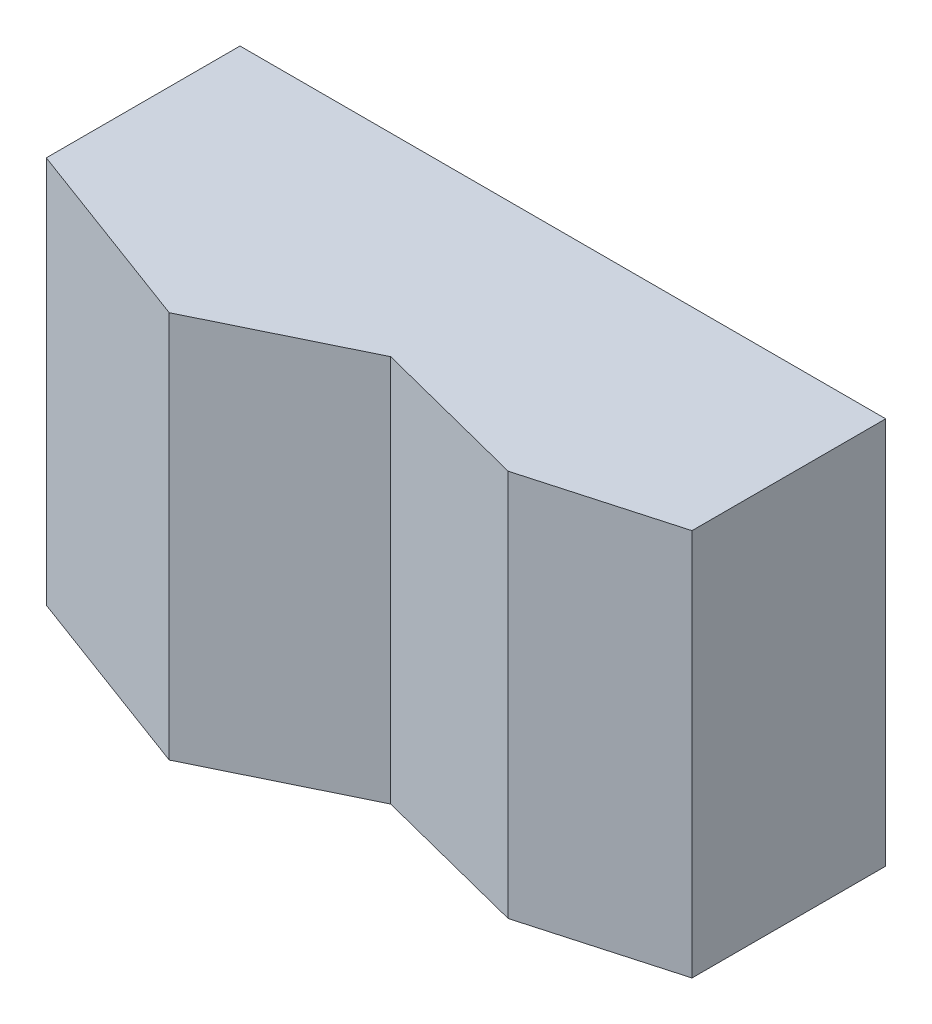
SolidWorks part; units mm, degrees
ref_plane "Front Plane" through (0, 0, 0) normal (0, 0, 1) x (1, 0, 0)
ref_plane "Top Plane" through (0, 0, 0) normal (0, 1, 0) x (1, 0, 0)
ref_plane "Right Plane" through (0, 0, 0) normal (1, 0, 0) x (0, 0, -1)
sketch "Sketch1" plane through (0, 0, 0) normal (0, 0, 1) x (1, 0, 0)
  line L1 (0, 0) -> (10, 0)
  line L2 (0, 0) -> (0, 6)
  line L3 (0, 6) -> (10, 6)
  line L4 (10, 0) -> (10, 6)
  dimension "D1" = 10
  dimension "D2" = 6
extrude "Boss-Extrude1" add sketch "Sketch1" along normal blind 3
sketch "Sketch2" plane through (0, 0, 0) normal (0, -1, 0) x (1, 0, 0)
  line L0 (0, 3) -> (3.0287, 4.1249)
  line L1 (3.0287, 4.1249) -> (5.3338, 3)
  line L2 (0, 3) -> (10, 3) construction
  line L3 (5.3338, 3) -> (7.7795, 3.6259)
  line L4 (7.7795, 3.6259) -> (10, 3)
  line L5 (10, 3) -> (0, 3)
  line M3 (10, 3) -> (0, 3)
extrude "Boss-Extrude2" add sketch "Sketch2" against normal blind 6 contours L1 L0 M3 | L4 L3 M3
sketch "Sketch3" plane through (0, 0, 0) normal (0, 0, -1) x (-1, 0, 0)
  line L0 (-10, 6) -> (0, 6) construction
  line L1 (-3, 4.5) -> (-2.5, 4.5)
  line L2 (-3, 4.5) -> (-3, 2.5)
  line L3 (-3, 2.5) -> (-2.5, 2.5)
  line L4 (-2.5, 4.5) -> (-2.5, 2.5)
  line L5 (-7, 4.5) -> (-6, 4.5)
  line L6 (-7, 4.5) -> (-7, 1.5)
  line L7 (-7, 1.5) -> (-6, 1.5)
  line L8 (-6, 4.5) -> (-6, 1.5)
  line L9 (-10, 0) -> (-10, 6) construction
  line L10 (0, 6) -> (0, 0) construction
  dimension "D1" = 1.5
  dimension "D2" = 3
  dimension "D3" = 1
  dimension "D4" = 3
  dimension "D5" = 0.5
  dimension "D6" = 3
  dimension "D7" = 1.5
  dimension "D8" = 2
extrude "Cut-Extrude1" cut sketch "Sketch3" against normal blind 1.5
